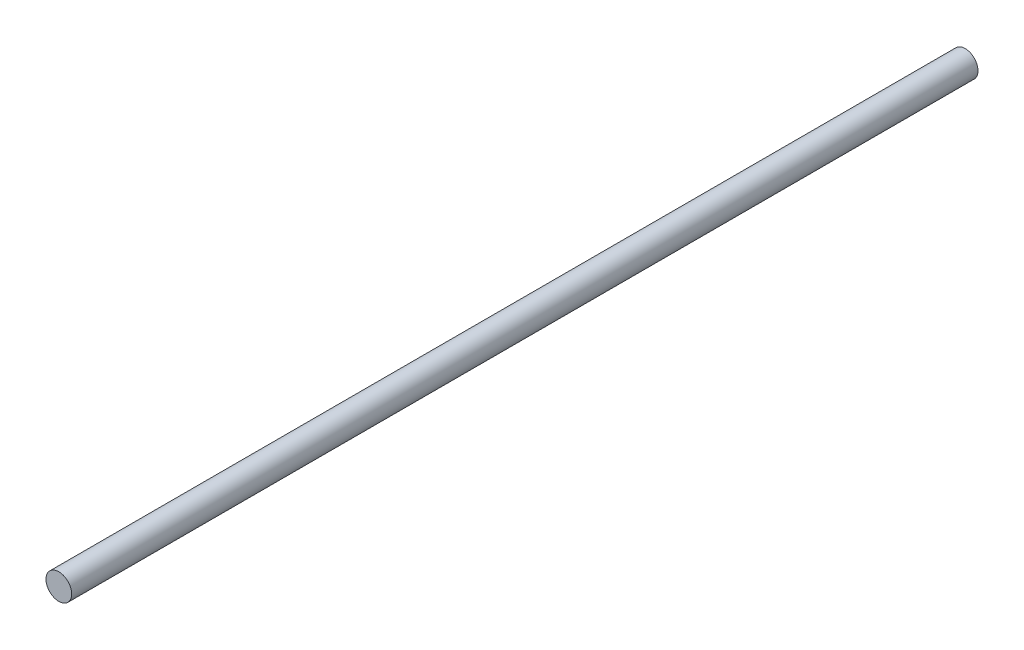
SolidWorks part; units mm, degrees
ref_plane "Front" through (0, 0, 0) normal (0, 0, 1) x (1, 0, 0)
ref_plane "Top" through (0, 0, 0) normal (0, 1, 0) x (1, 0, 0)
ref_plane "Right" through (0, 0, 0) normal (1, 0, 0) x (0, 0, -1)
sketch "Эскиз1" plane through (0, 0, 0) normal (0, 0, 1) x (1, 0, 0)
  circle A0 centre (0, 0) radius 4
extrude "Бобышка-Вытянуть1" add sketch "Эскиз1" along normal blind 282
